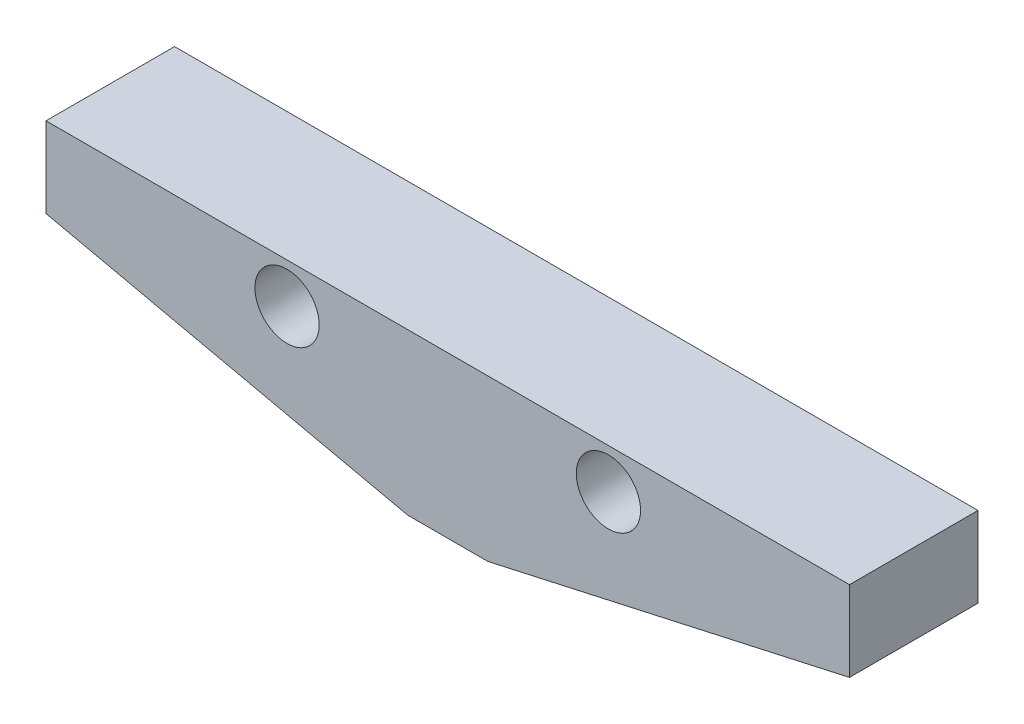
SolidWorks part; units mm, degrees
material "6061 Сплав"
ref_plane "Front" through (0, 0, 0) normal (0, 0, 1) x (1, 0, 0)
ref_plane "Top" through (0, 0, 0) normal (0, 1, 0) x (1, 0, 0)
ref_plane "Right" through (0, 0, 0) normal (1, 0, 0) x (0, 0, -1)
sketch "Эскиз1" plane through (0, 0, 0) normal (0, 0, 1) x (1, 0, 0)
  line L0 (-25.8561, 13.7576) -> (24.1439, 13.7576)
  line L1 (24.1439, 13.7576) -> (24.1439, 8.7576)
  line L2 (24.1439, 8.7576) -> (1.6439, 3.7576)
  line L3 (1.6439, 3.7576) -> (-3.3561, 3.7576)
  line L4 (-3.3561, 3.7576) -> (-25.8561, 8.7576)
  line L5 (-25.8561, 8.7576) -> (-25.8561, 13.7576)
  dimension "D1" = 50
  dimension "D2" = 5
  dimension "D3" = 5
  dimension "D4" = 50
  dimension "D5" = 10
  dimension "D6" = 5
  dimension "D7" = 22.5
extrude "Бобышка-Вытянуть1" add sketch "Эскиз1" along normal blind 8
sketch "Эскиз2" plane through (0, 0, 8) normal (0, 0, 1) x (1, 0, 0)
  line L0 (-25.8561, 13.7576) -> (-25.8561, 8.7576) construction
  line L1 (24.1439, 13.7576) -> (-25.8561, 13.7576) construction
  circle A0 centre (-10.8561, 11.2576) radius 1.25
  circle A1 centre (9.1439, 11.2576) radius 1.25
  dimension "D1" = 20
  dimension "D2" = 15
  dimension "D3" = 2.5
  dimension "D4" = 2.5
extrude "Вырез-Вытянуть1" cut sketch "Эскиз2" against normal blind 8
sketch "Эскиз3" plane through (0, 0, 8) normal (0, 0, 1) x (1, 0, 0)
  circle A0 centre (-10.8561, 11.2576) radius 2
  circle A1 centre (9.1439, 11.2576) radius 2
extrude "Вырез-Вытянуть2" cut sketch "Эскиз3" against normal blind 4
